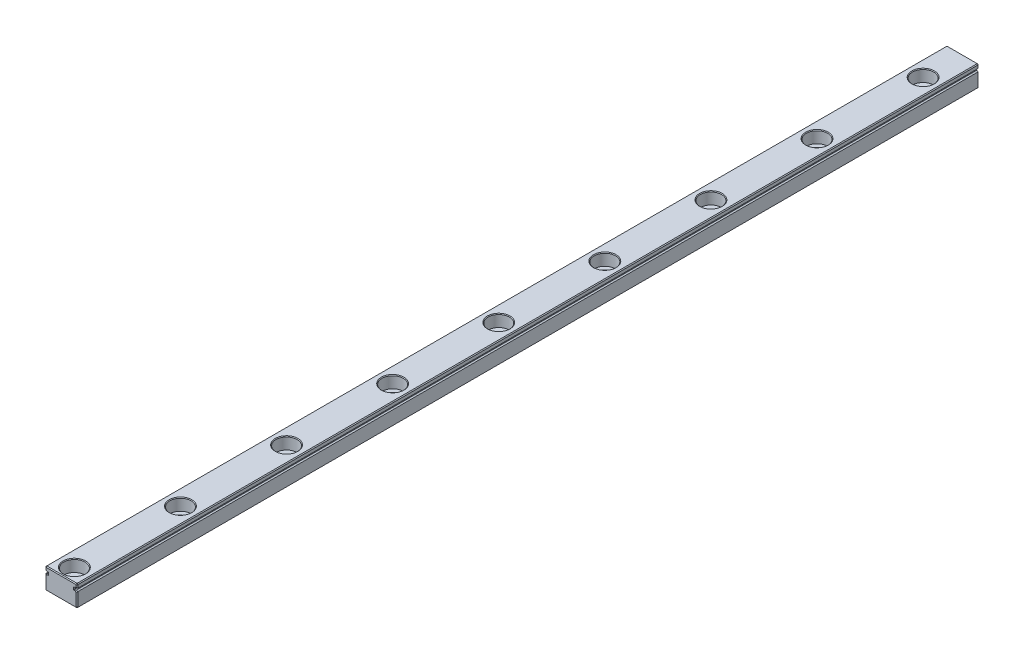
SolidWorks part; units mm, degrees
material "AISI 304"
ref_plane "Front Plane" through (0, 0, 0) normal (0, 0, 1) x (1, 0, 0)
ref_plane "Top Plane" through (0, 0, 0) normal (0, 1, 0) x (1, 0, 0)
ref_plane "Right Plane" through (0, 0, 0) normal (1, 0, 0) x (0, 0, -1)
sketch "Sketch1" plane through (0, 0, 0) normal (0, 0, 1) x (1, 0, 0)
  line L0 (0, 0) -> (0, 8) construction
  line L1 (0, 8) -> (12, 8)
  line L2 (0, 0) -> (12, 0)
  line L3 (0, 8) -> (0, 6.75)
  line L4 (0, 6.75) -> (0.5, 6.25) construction
  line L5 (0.5, 6.25) -> (1, 6.25)
  line L6 (0.5, 5.75) -> (0, 5.25) construction
  line L7 (0, 5.25) -> (0, 0)
  line L8 (1, 6.25) -> (1, 5.75)
  line L9 (1, 5.75) -> (0.5, 5.75)
  line L10 (0.5, 5.75) -> (0.75, 6) construction
  line L11 (0.75, 6) -> (0.5, 6.25) construction
  line L12 (0, 6.75) -> (0, 6.559)
  line L13 (0, 5.25) -> (0, 5.441)
  line L14 (6, 8) -> (6, 0) construction
  line L15 (11.25, 6) -> (11.5, 6.25) construction
  line L16 (11.5, 5.75) -> (11.25, 6) construction
  line L17 (11.5, 5.75) -> (12, 5.25) construction
  line L18 (12, 6.75) -> (11.5, 6.25) construction
  line L19 (12, 0) -> (12, 8) construction
  line L20 (12, 5.25) -> (12, 5.441)
  line L21 (12, 6.75) -> (12, 6.559)
  line L22 (11, 5.75) -> (11.5, 5.75)
  line L23 (11, 6.25) -> (11, 5.75)
  line L24 (12, 5.25) -> (12, 0)
  line L25 (11.5, 6.25) -> (11, 6.25)
  line L26 (12, 8) -> (12, 6.75)
  arc A0 (0, 5.441) -> (0.5, 5.75) centre (0, 6) ccw
  arc A1 (0.5, 6.25) -> (0, 6.559) centre (0, 6) ccw
  arc A2 (11.5, 6.25) -> (12, 6.559) centre (12, 6) cw
  arc A3 (12, 5.441) -> (11.5, 5.75) centre (12, 6) cw
  point P4 (1, 6)
  point P28 (11, 6)
  dimension "D1" = 8
  dimension "D2" = 6
  dimension "D3" = 0.5
  dimension "D4" = 45
  dimension "D5" = 2
  dimension "D6" = 1
extrude "Boss-Extrude1" add sketch "Sketch1" along normal blind 470
chamfer "Chamfer1" distance 0.3 angle 45 36 edges at (0, 0, 235) (12, 0, 235) (0, 8, 235) (12, 8, 235) (0.2939, 5.5245, 470) (0.75, 5.75, 470) (1, 6, 470) (0.75, 6.25, 470) (0.2939, 6.4755, 470) (0, 7.2795, 470) (6, 8, 470) (12, 7.2795, 470) (11.7061, 6.4755, 470) (11.25, 6.25, 470) (11, 6, 470) (11.25, 5.75, 470) (11.7061, 5.5245, 470) (12, 2.7205, 470) (6, 0, 470) (0, 2.7205, 470) (12, 2.7205, 0) (11.7061, 5.5245, 0) (11.25, 5.75, 0) (11, 6, 0) (11.25, 6.25, 0) (11.7061, 6.4755, 0) (12, 7.2795, 0) (6, 0, 0) (0, 2.7205, 0) (0.2939, 5.5245, 0) (0.75, 5.75, 0) (1, 6, 0) (0.75, 6.25, 0) (0.2939, 6.4755, 0) (0, 7.2795, 0) (6, 8, 0)
hole_wizard "CBORE for M5 Hex Head Bolt1" positions "3DSketch1" profile "Sketch3" counterbore size "M5" standard "ANSI Metric" end condition through all
sketch3d "3DSketch1"
  line L0 (6, 8, 0) -> (6, 8, 15) construction
  line L1 (11.7, 8, 0) -> (0.3, 8, 0) construction
  point P0 (6, 8, 15)
  dimension "D1" = 15
sketch "Sketch3" plane through (6, 8, 15) normal (1, 0, 0) x (0, 0, 1)
  line L0 (0, 0) -> (0, 8)
  line L1 (2.25, 7.75) -> (2.5, 8)
  line L2 (4, 4.5) -> (2.25, 4.5)
  line L3 (2.25, 4.5) -> (2.25, 7.75)
  line L5 (4, 4.5) -> (4, 0.25)
  line L6 (4, 0.25) -> (4.25, 0)
  line L7 (4.25, 0) -> (0, 0)
  line L8 (-4, 0.25) -> (-4.25, 0) construction
  line L11 (0, -6.35) -> (0, 107.95) construction
  line L12 (2.5, 8) -> (0, 8)
  line L13 (-2.25, 7.75) -> (-2.5, 8) construction
  dimension "Thru Hole Dia." = 4.5
  dimension "Thru Hole Depth" = 8
  dimension "C'Bore Dia." = 8
  dimension "C'Bore Depth" = 4.5
  dimension "Near C'Sink Dia." = 8.5
  dimension "Near C'Sink Angle" = 90
  dimension "Far C'Sink Dia." = 5
  dimension "Far C'Sink Angle" = 90
pattern_linear "LPattern1" count 12 spacing 40 along (0, 0, 1) of "CBORE for M5 Hex Head Bolt1"
sketch "Croquis1" plane through (0, 0, 470) normal (0, 0, 1) x (1, 0, 0)
  line L1 (-4.1596, 9.8274) -> (14.7316, 9.8274)
  line L2 (-4.1596, 9.8274) -> (-4.1596, -2.5781)
  line L3 (-4.1596, -2.5781) -> (14.7316, -2.5781)
  line L4 (14.7316, 9.8274) -> (14.7316, -2.5781)
extrude "Cortar-Extruir2" cut sketch "Croquis1" against normal blind 130
chamfer "Chaflán1" distance 0.3 angle 45 20 edges at (12, 2.8705, 340) (11.85, 0.15, 340) (6, 0, 340) (0.15, 0.15, 340) (0, 2.8705, 340) (0.2939, 5.5245, 340) (0.75, 5.75, 340) (1, 6, 340) (0.75, 6.25, 340) (0.2939, 6.4755, 340) (0, 7.1295, 340) (0.15, 7.85, 340) (6, 8, 340) (11.85, 7.85, 340) (12, 7.1295, 340) (11.7061, 6.4755, 340) (11.25, 6.25, 340) (11, 6, 340) (11.25, 5.75, 340) (11.7061, 5.5245, 340)
